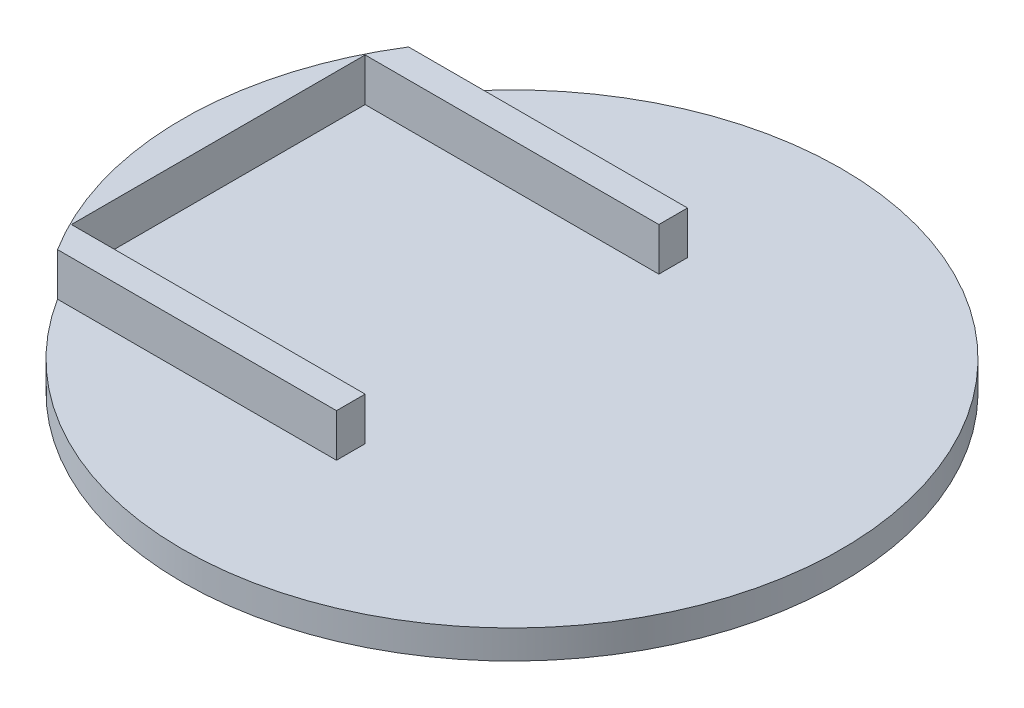
SolidWorks part; units mm, degrees
ref_plane "Front Plane" through (0, 0, 0) normal (0, 0, 1) x (1, 0, 0)
ref_plane "Top Plane" through (0, 0, 0) normal (0, 1, 0) x (1, 0, 0)
ref_plane "Right Plane" through (0, 0, 0) normal (1, 0, 0) x (0, 0, -1)
sketch "Sketch1" plane through (0, 0, 0) normal (0, 1, 0) x (1, 0, 0)
  circle A0 centre (0, 0) radius 23
  dimension "D1" = 46
extrude "Boss-Extrude1" add sketch "Sketch1" along normal blind 2
ref_plane "Plane1" through (0, 0, 0) normal (0, 1, 0) x (1, 0, 0)
sketch "Sketch3" plane through (0, 0, 0) normal (0, 1, 0) x (1, 0, 0)
  circle A0 centre (0, 0) radius 0.5
  dimension "D1" = 1
extrude "Cut-Extrude2" cut sketch "Sketch3" along normal blind 1
sketch "Sketch4" plane through (0, 0, 0) normal (0, 1, 0) x (1, 0, 0)
  line L0 (0, 0) -> (0, 16.7478) construction
  line L1 (0, 0) -> (-10.25, 0) construction
  line L2 (0, 10.25) -> (0, 12.25)
  line L3 (0, 10.25) -> (-20.5, 10.25)
  line L4 (0, 10.25) -> (0, -10.25) construction
  line L5 (0, -10.25) -> (-20.5, -10.25)
  line L6 (-20.5, 10.25) -> (-20.5, -10.25)
  line L7 (0, 10.25) -> (-20.5, -10.25) construction
  line L8 (0, -10.25) -> (-20.5, 10.25) construction
  line L9 (0, 12.25) -> (-19.4663, 12.25)
  line L10 (0, -10.25) -> (0, -12.25)
  line L11 (0, -12.25) -> (-19.4663, -12.25)
  circle A0 centre (0, 0) radius 23 construction
  arc A1 (-19.4663, 12.25) -> (-19.4663, -12.25) centre (0, 0) ccw
  dimension "D1" = 20.5
  dimension "D2" = 20.5
  dimension "D3" = 2
  dimension "D4" = 2
extrude "Boss-Extrude2" add sketch "Sketch4" along normal blind 5
